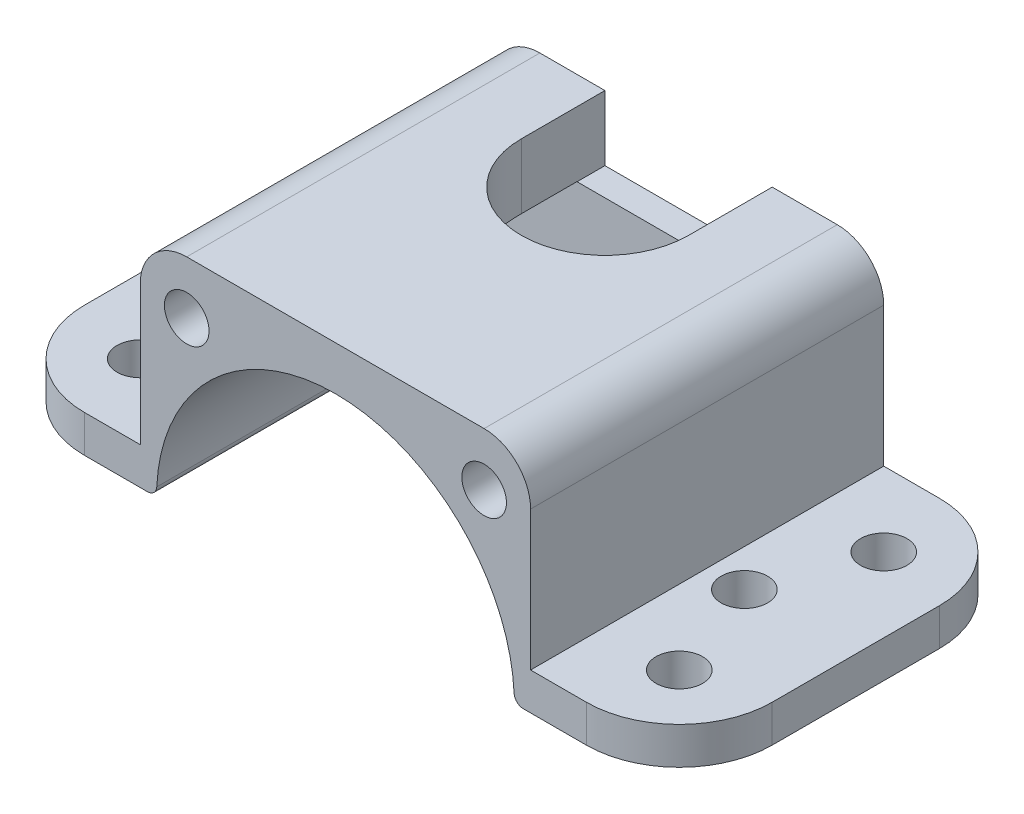
SolidWorks part; units mm, degrees
ref_plane "Front Plane" through (0, 0, 0) normal (0, 0, 1) x (1, 0, 0)
ref_plane "Top Plane" through (0, 0, 0) normal (0, 1, 0) x (1, 0, 0)
ref_plane "Right Plane" through (0, 0, 0) normal (1, 0, 0) x (0, 0, -1)
sketch "Sketch1" plane through (0, 0, 0) normal (0, 0, 1) x (1, 0, 0)
  line L1 (-21, -24) -> (21, -24)
  line L2 (-21, -24) -> (-21, 24)
  line L3 (-21, 24) -> (21, 24)
  line L4 (21, -24) -> (21, 24)
  line L5 (-21, -24) -> (21, 24) construction
  line L6 (-21, 24) -> (21, -24) construction
  circle A0 centre (0, 0) radius 19.25
  circle A1 centre (-16, 18.2857) radius 2.4
  circle A2 centre (16, 18.2857) radius 2.4
  circle A3 centre (16, -18.2857) radius 2.4
  circle A4 centre (-16, -18.2857) radius 2.4
  point P0 (0, 0)
  dimension "D3" = 38.5
  dimension "D4" = 4.8
  dimension "D1" = 48
  dimension "D2" = 42
  dimension "D5" = 5
extrude "Boss-Extrude1" add sketch "Sketch1" against normal blind 35
sketch "Sketch4" plane through (0, 0, 0) normal (0, 0, 1) x (1, 0, 0)
  line L1 (-21, -24) -> (-40, -24)
  line L2 (-21, -24) -> (-21, -19)
  line L3 (-21, -19) -> (-40, -19)
  line L4 (-40, -24) -> (-40, -19)
  line L5 (21, -24) -> (40, -24)
  line L6 (21, -24) -> (21, -19)
  line L7 (21, -19) -> (40, -19)
  line L8 (40, -24) -> (40, -19)
  dimension "D1" = 5
  dimension "D2" = 80
extrude "Boss-Extrude3" add sketch "Sketch4" against normal up to surface (35 mm away) up to face at (-13.6, -18.2857, -35)
sketch "Sketch5" plane through (0, -19, 0) normal (0, 1, 0) x (1, 0, 0)
  line L0 (-25, 19) -> (-40, 35) construction
  line L1 (25, 19) -> (40, 35) construction
  line L2 (-21, 35) -> (-40, 35) construction
  circle A0 centre (-25, 19) radius 2.5
  circle A1 centre (25, 19) radius 2.5
  dimension "D1" = 5
  dimension "D2" = 50
  dimension "D3" = 16
extrude "Cut-Extrude1" cut sketch "Sketch5" against normal up to next
sketch "Sketch6" plane through (0, 0, -35) normal (0, 0, -1) x (-1, 0, 0)
  line L8 (-21, 24) -> (-21, -19)
  line L9 (-21, -19) -> (-40, -19)
  line L10 (-40, -19) -> (-40, -24)
  line L11 (-40, -24) -> (40, -24)
  line L12 (40, -24) -> (40, -19)
  line L13 (40, -19) -> (21, -19)
  line L14 (21, -19) -> (21, 24)
  line L15 (21, 24) -> (-21, 24)
  line L16 (-21, 24) -> (-21, -19)
  line L17 (-21, -19) -> (-40, -19)
  line L18 (-40, -19) -> (-40, -24)
  line L19 (-40, -24) -> (40, -24)
  line L20 (40, -24) -> (40, -19)
  line L21 (40, -19) -> (21, -19)
  line L22 (21, -19) -> (21, 24)
  line L23 (21, 24) -> (-21, 24)
  dimension "D1" = 0
extrude "Boss-Extrude4" add sketch "Sketch6" along normal blind 3
sketch "Sketch7" plane through (0, 0, 0) normal (0, 0, 1) x (1, 0, 0)
  line L0 (-21, 24) -> (-21, -19) construction
  line L1 (-21, 0) -> (21, 0)
  line L5 (-21, 0) -> (-21, -19)
  line L6 (-21, -19) -> (-40, -19)
  line L7 (-40, -19) -> (-40, -24)
  line L8 (-40, -24) -> (40, -24)
  line L9 (40, -24) -> (40, -19)
  line L10 (40, -19) -> (21, -19)
  line L11 (21, -19) -> (21, 0)
  dimension "D1" = 0
extrude "Cut-Extrude2" cut sketch "Sketch7" against normal up to next
sketch "Sketch9" plane through (0, 0, 0) normal (0, 0, 1) x (1, 0, 0)
  line L1 (-21, 0) -> (-37, 0)
  line L2 (-21, 0) -> (-21, 4)
  line L3 (-21, 4) -> (-37, 4)
  line L4 (-37, 0) -> (-37, 4)
  line L5 (21, 0) -> (37, 0)
  line L6 (21, 0) -> (21, 4)
  line L7 (21, 4) -> (37, 4)
  line L8 (37, 0) -> (37, 4)
  dimension "D1" = 16
  dimension "D2" = 4
extrude "Boss-Extrude6" add sketch "Sketch9" against normal up to surface (38 mm away) up to face at (0, 12, -38)
sketch "Sketch10" plane through (0, 4, 0) normal (0, 1, 0) x (1, 0, 0)
  line L0 (0, -1000) -> (0, 49000) construction
  line L1 (-29, 30) -> (-37, 38) construction
  line L2 (-29, 8) -> (-37, 0) construction
  line L3 (-37, 38) -> (-37, 0) construction
  line L4 (29, 8) -> (37, 0) construction
  line L5 (29, 30) -> (37, 38) construction
  circle A0 centre (-29, 8) radius 2.5
  circle A1 centre (-29, 30) radius 2.5
  circle A2 centre (29, 30) radius 2.5
  circle A3 centre (29, 8) radius 2.5
  circle A4 centre (-25, 19) radius 2.5
  circle A5 centre (25, 19) radius 2.5
  dimension "D1" = 5
  dimension "D2" = 22
  dimension "D4" = 4
  dimension "D3" = 8
  dimension "D5" = 11
extrude "Cut-Extrude3" cut sketch "Sketch10" against normal up to next
fillet "Fillet1" radius 10 4 edges at (37, 2, -38) (37, 2, 0) (-37, 2, -38) (-37, 2, 0)
fillet "Fillet2" radius 5 2 edges at (21, 24, -19) (-21, 24, -19)
sketch "Sketch11" plane through (0, 0, -35) normal (0, 0, 1) x (1, 0, 0)
  circle A0 centre (16, 18.2857) radius 2.4 construction
  circle A1 centre (-16, 18.2857) radius 2.4 construction
  circle A2 centre (16, 18.2857) radius 2.4
  circle A3 centre (-16, 18.2857) radius 2.4
extrude "Cut-Extrude4" cut sketch "Sketch11" against normal through all
fillet "Fillet3" radius 1 2 edges at (19.25, 0, -17.5) (-19.25, 0, -17.5)
sketch "Sketch12" plane through (0, 24, 0) normal (0, 1, 0) x (1, 0, 0)
  line L0 (-16, 38) -> (16, 38) construction
  line L2 (-9, 29) -> (9, 29)
  line L3 (-9, 29) -> (-9, 38)
  line L4 (-9, 38) -> (9, 38)
  line L5 (9, 29) -> (9, 38)
  circle A0 centre (0, 29) radius 9
  line M3 (16, 38) -> (-16, 38)
  dimension "D1" = 18
  dimension "D2" = 9
extrude "Cut-Extrude7" cut sketch "Sketch12" against normal blind 7 contours L2 A0 | L2 A0 | A0 L5 M3 | A0 L4 L3
